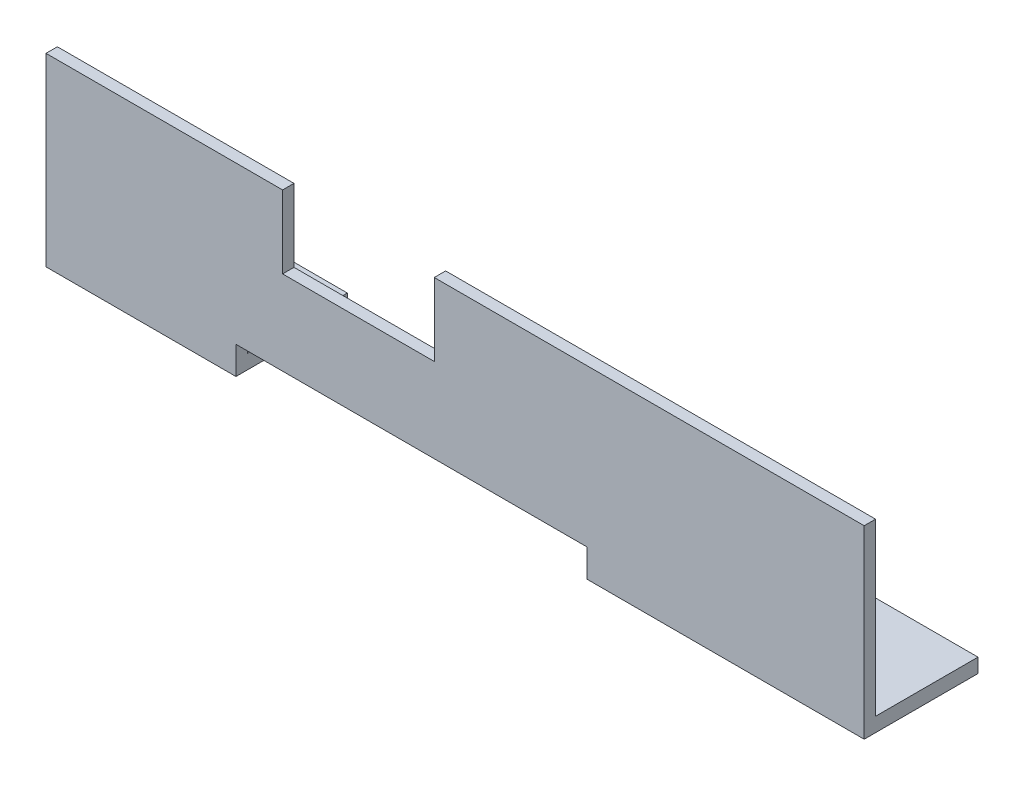
SolidWorks part; units mm, degrees
ref_plane "Спереди" through (0, 0, 0) normal (0, 0, 1) x (1, 0, 0)
ref_plane "Сверху" through (0, 0, 0) normal (0, 1, 0) x (1, 0, 0)
ref_plane "Справа" through (0, 0, 0) normal (1, 0, 0) x (0, 0, -1)
sketch "Эскиз1" plane through (0, 0, 0) normal (1, 0, 0) x (0, 0, -1)
  line L0 (0, 0) -> (0, 60)
  line L1 (0, 0) -> (36, 0)
  line L2 (36, 0) -> (36, -5)
  line L3 (36, -5) -> (-4, -5)
  line L4 (-4, -5) -> (-4, 60)
  line L5 (-4, 60) -> (0, 60)
extrude "Вытянуть1" add sketch "Эскиз1" along normal up to surface (287.5765 mm away)
sketch "Эскиз2" plane through (0, 0, -36) normal (0, 0, -1) x (-1, 0, 0)
  line L1 (-190.2228, 4.8196) -> (-66.7627, 4.8196)
  line L2 (-190.2228, 4.8196) -> (-190.2228, -10.755)
  line L3 (-190.2228, -10.755) -> (-66.7627, -10.755)
  line L4 (-66.7627, 4.8196) -> (-66.7627, -10.755)
extrude "Вырез-Вытянуть1" cut sketch "Эскиз2" against normal through all from offset 20
sketch "Эскиз3" plane through (0, 0, 0) normal (0, 0, -1) x (-1, 0, 0)
  line L1 (-136.4668, 64.4868) -> (-83.1623, 64.4868)
  line L2 (-136.4668, 64.4868) -> (-136.4668, 34.4358)
  line L3 (-136.4668, 34.4358) -> (-83.1623, 34.4358)
  line L4 (-83.1623, 64.4868) -> (-83.1623, 34.4358)
extrude "Вырез-Вытянуть2" cut sketch "Эскиз3" against normal blind 40
sketch "Эскиз4" plane through (0, 0, 0) normal (0, 1, 0) x (1, 0, 0)
  line L1 (65.9253, 36.8821) -> (154.5046, 36.8821)
  line L2 (65.9253, 36.8821) -> (65.9253, 29.8998)
  line L3 (65.9253, 29.8998) -> (154.5046, 29.8998)
  line L4 (154.5046, 36.8821) -> (154.5046, 29.8998)
extrude "Вырез-Вытянуть3" cut sketch "Эскиз4" against normal through all
